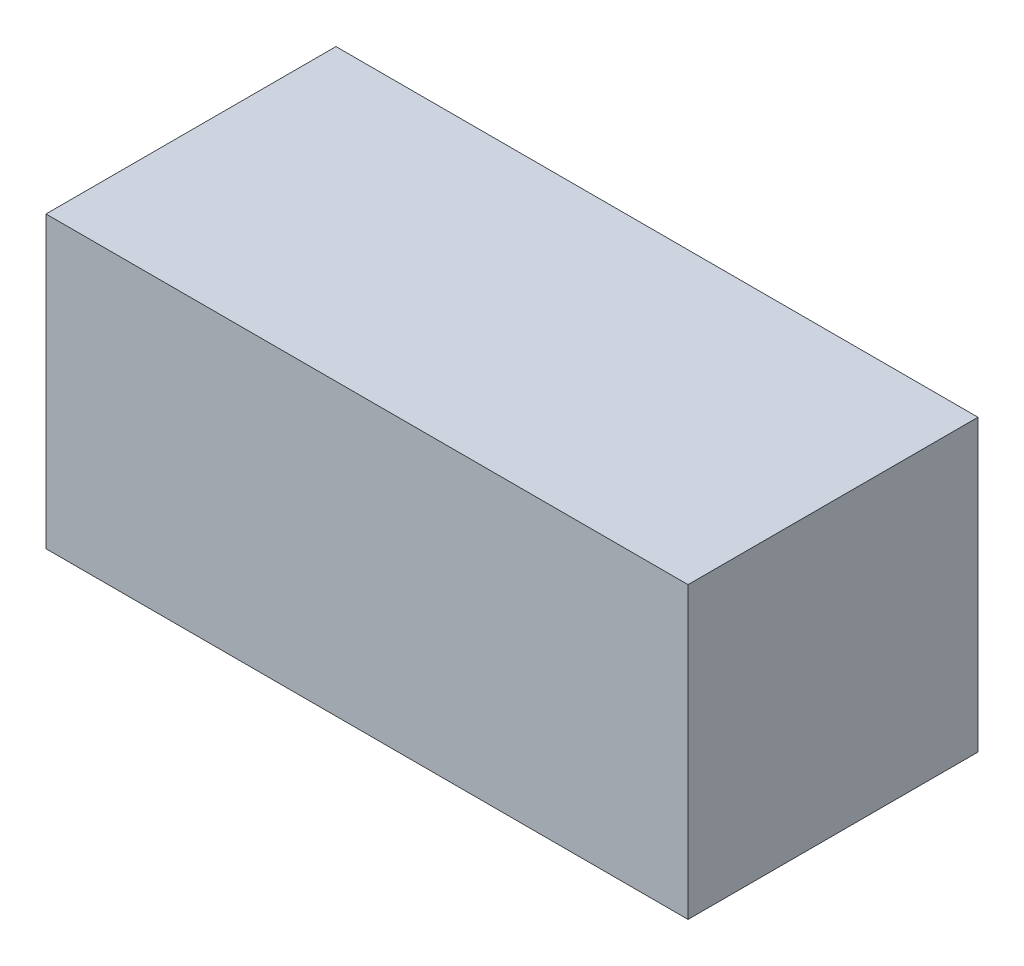
SolidWorks part; units mm, degrees
ref_plane "Plan de face" through (0, 0, 0) normal (0, 0, 1) x (1, 0, 0)
ref_plane "Plan de dessus" through (0, 0, 0) normal (0, 1, 0) x (1, 0, 0)
ref_plane "Plan de droite" through (0, 0, 0) normal (1, 0, 0) x (0, 0, -1)
sketch "Esquisse1" plane through (0, 0, 0) normal (0, 0, 1) x (1, 0, 0)
  line L1 (-65.1146, 23.6368) -> (89.8854, 23.6368)
  line L2 (-65.1146, 23.6368) -> (-65.1146, -46.3632)
  line L3 (-65.1146, -46.3632) -> (89.8854, -46.3632)
  line L4 (89.8854, 23.6368) -> (89.8854, -46.3632)
  dimension "D1" = 155
  dimension "D2" = 70
extrude "Boss.-Extru.1" add sketch "Esquisse1" along normal blind 70
sketch "Esquisse2" plane through (-65.1146, 0, 0) normal (-1, 0, 0) x (0, 0, 1)
  line L0 (70, 23.6368) -> (0, 23.6368) construction
  line L1 (66, 19.6368) -> (4, 19.6368)
  line L2 (66, 19.6368) -> (66, -42.3632)
  line L3 (66, -42.3632) -> (4, -42.3632)
  line L4 (4, 19.6368) -> (4, -42.3632)
  line L5 (70, 23.6368) -> (70, -46.3632) construction
  line L6 (70, -46.3632) -> (0, -46.3632) construction
  line L7 (0, 23.6368) -> (0, -46.3632) construction
  dimension "D1" = 4
  dimension "D2" = 4
  dimension "D3" = 4
  dimension "D4" = 4
extrude "Enlèv. mat.-Extru.1" cut sketch "Esquisse2" against normal blind 151
sketch "Esquisse3" plane through (0, -46.3632, 0) normal (0, -1, 0) x (1, 0, 0)
  line L0 (-65.1146, 70) -> (89.8854, 70) construction
  line L1 (-65.1146, 70) -> (-65.1146, 0) construction
  circle A0 centre (-60.1146, 35) radius 2.5
  circle A1 centre (49.8854, 35) radius 2.5
  dimension "D1" = 5
  dimension "D2" = 5
  dimension "D3" = 35
  dimension "D6" = 115
  dimension "D4" = 35
  dimension "D5" = 5
extrude "Enlèv. mat.-Extru.2" cut sketch "Esquisse3" against normal blind 5
